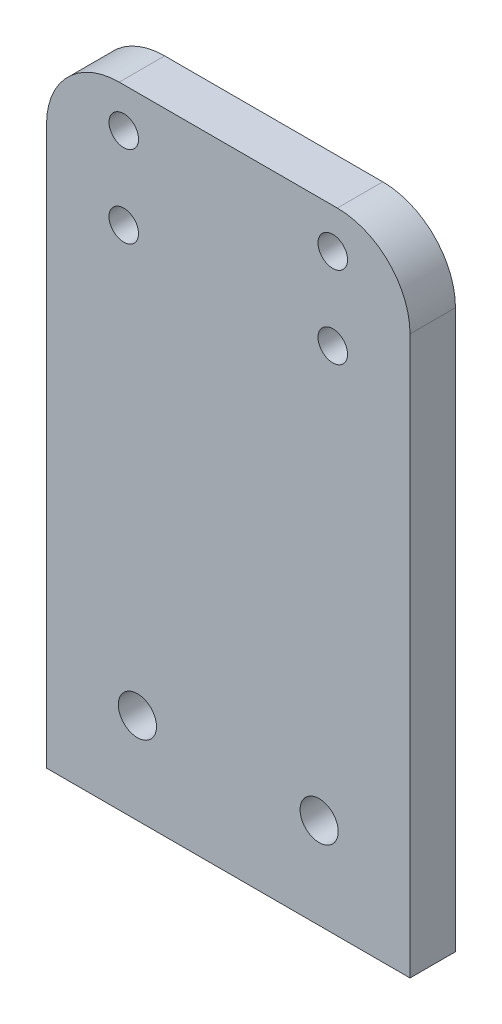
SolidWorks part; units mm, degrees
ref_plane "Front Plane" through (0, 0, 0) normal (0, 0, 1) x (1, 0, 0)
ref_plane "Top Plane" through (0, 0, 0) normal (0, 1, 0) x (1, 0, 0)
ref_plane "Right Plane" through (0, 0, 0) normal (1, 0, 0) x (0, 0, -1)
sketch "Sketch1" plane through (0, 0, 0) normal (0, 0, 1) x (1, 0, 0)
  line L1 (-1740.4212, -1861.9194) -> (-1820.4212, -1861.9194)
  line L2 (-1740.4212, -1861.9194) -> (-1740.4212, -1723.1646)
  line L3 (-1820.4212, -1723.1646) -> (-1740.4212, -1723.1646)
  line L4 (-1820.4212, -1861.9194) -> (-1820.4212, -1723.1646)
extrude "Boss-Extrude1" add sketch "Sketch1" along normal blind 10
hole_wizard "Foro per Vite M8-1" positions "Sketch3" profile "Sketch2" hole size "M8" standard "ISO" end condition through all
sketch "Sketch3" plane through (0, 0, 10) normal (0, 0, 1) x (1, 0, 0)
  point P0 (-1760.4212, -1841.9194)
  point P6 (-1800.4212, -1841.9194)
sketch "Sketch2" plane through (-1760.4212, -1841.9194, 10) normal (1, 0, 0) x (0, -1, 0)
  line L0 (0, 0) -> (0, 10)
  line L1 (0, 10) -> (4.2, 10)
  line L2 (4.2, 10) -> (4.2, 0)
  line L5 (4.2, 0) -> (0, 0)
  line L11 (0, -6.35) -> (0, 107.95) construction
  dimension "Thru Hole Dia." = 8.4
  dimension "Thru Hole Depth" = 10
sketch "Schizzo1" plane through (0, 0, 10) normal (0, 0, 1) x (1, 0, 0)
  circle A12 centre (-1803.4212, -1731.9194) radius 3.25
  circle A13 centre (-1803.4212, -1749.9194) radius 3.25
  circle A14 centre (-1757.4212, -1731.9194) radius 3.25
  circle A15 centre (-1757.4212, -1749.9194) radius 3.25
extrude "Taglio-Estrusione1" cut sketch "Schizzo1" against normal through all
fillet "Raccordo1" radius 16 2 edges at (-1740.4212, -1723.1646, 5) (-1820.4212, -1723.1646, 5)
